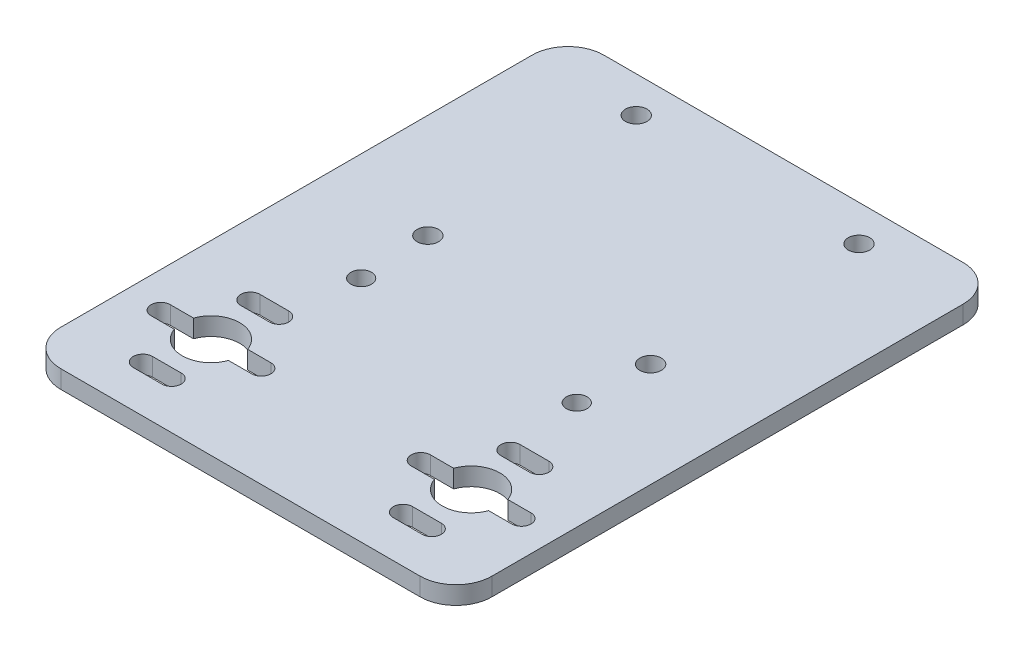
SolidWorks part; units mm, degrees
ref_plane "Front Plane" through (0, 0, 0) normal (0, 0, 1) x (1, 0, 0)
ref_plane "Top Plane" through (0, 0, 0) normal (0, 1, 0) x (1, 0, 0)
ref_plane "Right Plane" through (0, 0, 0) normal (1, 0, 0) x (0, 0, -1)
sketch "Sketch1" plane through (0, 0, 0) normal (0, 1, 0) x (1, 0, 0)
  line L1 (-38.1, 19.05) -> (38.1, 19.05)
  line L2 (-38.1, 19.05) -> (-38.1, -19.05)
  line L3 (-38.1, -19.05) -> (38.1, -19.05)
  line L4 (38.1, 19.05) -> (38.1, -19.05)
  line L5 (-38.1, 19.05) -> (38.1, -19.05) construction
  line L6 (-38.1, -19.05) -> (38.1, 19.05) construction
  point P0 (0, 0)
  dimension "D1" = 38.1
  dimension "D2" = 76.2
extrude "Boss-Extrude1" add sketch "Sketch1" along normal blind 3.175
sketch "Sketch3" plane through (0, 0, 0) normal (0, -1, 0) x (1, 0, 0)
  line L4 (-20.447, 10.77) -> (-25.527, 10.77) construction
  line L5 (-20.447, 9.07) -> (-25.527, 9.07)
  line L6 (-20.447, 12.47) -> (-25.527, 12.47)
  line L7 (0, -22.6688) -> (0, 2.1978) construction
  line L8 (-25.527, -8.23) -> (-20.447, -8.23) construction
  line L9 (-25.527, -6.53) -> (-20.447, -6.53)
  line L10 (-25.527, -9.93) -> (-20.447, -9.93)
  line L11 (-31.877, 1.27) -> (-14.097, 1.27) construction
  line L12 (-31.877, 2.97) -> (-14.097, 2.97)
  line L13 (-31.877, -0.43) -> (-14.097, -0.43)
  circle A6 centre (-22.987, 1.27) radius 5.08
  arc A7 (-20.447, 9.07) -> (-20.447, 12.47) centre (-20.447, 10.77) ccw
  arc A8 (-25.527, 12.47) -> (-25.527, 9.07) centre (-25.527, 10.77) ccw
  arc A9 (-25.527, -6.53) -> (-25.527, -9.93) centre (-25.527, -8.23) ccw
  arc A10 (-20.447, -9.93) -> (-20.447, -6.53) centre (-20.447, -8.23) ccw
  arc A11 (-31.877, 2.97) -> (-31.877, -0.43) centre (-31.877, 1.27) ccw
  arc A12 (-14.097, -0.43) -> (-14.097, 2.97) centre (-14.097, 1.27) ccw
  point P0 (-22.987, -8.23)
  point P12 (-22.987, -8.23)
  point P20 (-22.987, 10.77)
  point P30 (-22.987, 1.27)
  point P33 (0, 0)
  point P36 (-22.987, -1.7)
  point P37 (0, 0)
  point P38 (-22.987, 0)
  point P39 (-22.987, -1.6053)
  point P40 (-22.987, -3.5198)
  point P41 (-22.987, -5.3042)
  point P42 (-22.987, 0)
  point P43 (0, 0)
  point P44 (0, 0)
  dimension "D3" = 22.987
  dimension "D7" = 10.16
  dimension "D2" = 19
  dimension "D4" = 3.4
  dimension "D5" = 3.4
  dimension "D6" = 17.78
  dimension "D8" = 3.4
  dimension "D9" = 5.08
  dimension "D10" = 9.5
  dimension "D11" = 1.27
extrude "Cut-Extrude1" cut sketch "Sketch3" against normal through all contours L6 A8 L5 A7 | L12 A11 L13 A6 | L13 A6 L12 | L12 A6 | L13 A12 L12 A6 | L13 A6 | L10 A10 L9 A9
mirror "Mirror1" about plane through (0, 0, 0) normal (1, 0, 0) of "Cut-Extrude1"
sketch "Sketch5" plane through (0, 0, 0) normal (0, 1, 0) x (1, 0, 0)
  line L0 (38.1, -19.05) -> (38.1, 19.05) construction
  line L1 (-38.1, 19.05) -> (38.1, 19.05)
  line L2 (-38.1, 19.05) -> (-38.1, 76.9366)
  line L3 (-38.1, 76.9366) -> (38.1, 76.9366)
  line L4 (38.1, 19.05) -> (38.1, 76.9366)
  dimension "D1" = 57.8866
extrude "Boss-Extrude3" add sketch "Sketch5" along normal blind 3.175
hole_wizard "#6 Clearance Hole1" positions "Sketch7" profile "Sketch8" hole size "#6" standard "ANSI Inch" end condition through all
sketch "Sketch7" plane through (0, 3.175, 0) normal (0, 1, 0) x (1, 0, 0)
  line L0 (0, 0) -> (0, 42.8107) construction
  line L2 (-38.1, -19.05) -> (38.1, -19.05) construction
  point P2 (-19.05, 21.336)
  point P6 (19.05, 21.336)
  dimension "D1" = 19.05
  dimension "D4" = 40.386
sketch "Sketch8" plane through (-19.05, 3.175, -21.336) normal (1, 0, 0) x (0, 0, 1)
  line L0 (0, 0) -> (0, 3.175)
  line L1 (0, 3.175) -> (1.8288, 3.175)
  line L2 (1.8288, 3.175) -> (1.8288, 0)
  line L5 (1.8288, 0) -> (0, 0)
  line L11 (0, -6.35) -> (0, 107.95) construction
  dimension "Thru Hole Dia." = 3.6576
  dimension "Thru Hole Depth" = 3.175
fillet "Fillet1" radius 6.35 4 edges at (38.1, 1.5875, -76.9366) (38.1, 1.5875, 19.05) (-38.1, 1.5875, -76.9366) (-38.1, 1.5875, 19.05)
hole_wizard "#6 Clearance Hole2" positions "Sketch10" profile "Sketch11" hole size "#6" standard "ANSI Inch" end condition through all
sketch "Sketch10" plane through (0, 0, 0) normal (0, -1, 0) x (-1, 0, 0)
  line L0 (38.1, 70.5866) -> (38.1, -12.7) construction
  line L1 (-38.1, -12.7) -> (-38.1, 70.5866) construction
  line L2 (-31.75, 76.9366) -> (31.75, 76.9366) construction
  point P0 (19.685, 70.5866)
  point P2 (19.685, 33.7566)
  point P4 (-19.685, 70.5866)
  point P6 (-19.685, 33.7566)
  dimension "D1" = 18.415
  dimension "D2" = 18.415
  dimension "D3" = 6.35
  dimension "D5" = 36.83
sketch "Sketch11" plane through (-19.685, 0, -70.5866) normal (1, 0, 0) x (0, 0, -1)
  line L0 (0, 0) -> (0, 3.175)
  line L1 (0, 3.175) -> (1.8986, 3.175)
  line L2 (1.8986, 3.175) -> (1.8986, 0)
  line L5 (1.8986, 0) -> (0, 0)
  line L11 (0, -6.35) -> (0, 107.95) construction
  dimension "Thru Hole Dia." = 3.7973
  dimension "Thru Hole Depth" = 3.175
